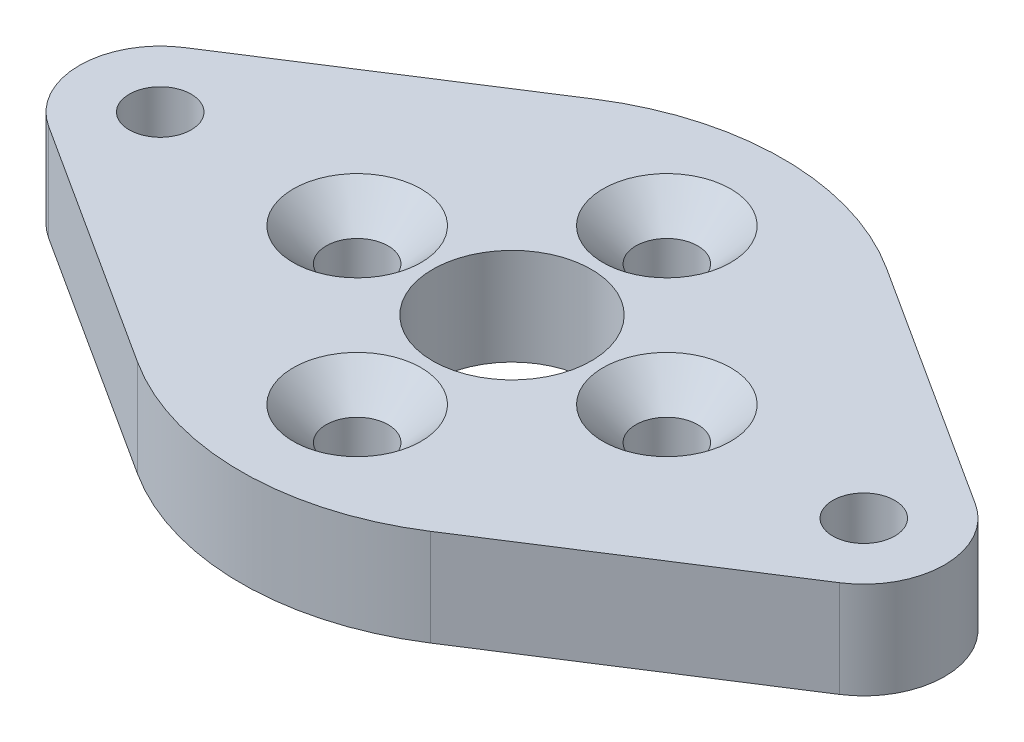
SolidWorks part; units mm, degrees
material "ABS"
ref_plane "Front Plane" through (0, 0, 0) normal (0, 0, 1) x (1, 0, 0)
ref_plane "Top Plane" through (0, 0, 0) normal (0, 1, 0) x (1, 0, 0)
ref_plane "Right Plane" through (0, 0, 0) normal (1, 0, 0) x (0, 0, -1)
sketch "Sketch1" plane through (0, 0, 0) normal (0, 1, 0) x (1, 0, 0)
  line L0 (18.1754, 0) -> (-18.1754, 0) construction
  line L1 (0, 0) -> (0, 8) construction
  line L2 (-20.4324, 3.5129) -> (-7.5676, 11.7784)
  line L3 (-21.3509, 0) -> (-19.7631, -2.75) construction
  line L4 (-19.7631, -2.75) -> (-16.5877, -2.75) construction
  line L5 (-16.5877, -2.75) -> (-15, 0) construction
  line L6 (-15, 0) -> (-16.5877, 2.75) construction
  line L7 (-16.5877, 2.75) -> (-19.7631, 2.75) construction
  line L8 (-19.7631, 2.75) -> (-21.3509, 0) construction
  line L9 (-20.4324, -3.5129) -> (-7.5676, -11.7784)
  line L10 (0, 0) -> (0, 17.7952) construction
  line L11 (20.4324, -3.5129) -> (7.5676, -11.7784)
  line L12 (20.4324, 3.5129) -> (7.5676, 11.7784)
  circle A0 centre (0, 0) radius 8 construction
  circle A1 centre (0, 0) radius 4.1
  arc A6 (-7.5676, -11.7784) -> (7.5676, -11.7784) centre (0, 0) ccw
  circle A7 centre (-18.1754, 0) radius 1.6
  circle A8 centre (18.1754, 0) radius 1.6
  circle A9 centre (-18.1754, 0) radius 2.75 construction
  arc A10 (-20.4324, 3.5129) -> (-20.4324, -3.5129) centre (-18.1754, 0) ccw
  arc A11 (20.4324, 3.5129) -> (20.4324, -3.5129) centre (18.1754, 0) cw
  arc A12 (7.5676, 11.7784) -> (-7.5676, 11.7784) centre (0, 0) ccw
  circle A13 centre (8, 0) radius 1.6
  circle A14 centre (0, 8) radius 1.6
  circle A15 centre (-8, 0) radius 1.6
  circle A16 centre (0, -8) radius 1.6
  point P9 (0, 0)
  dimension "D1" = 16
  dimension "D2" = 8.2
  dimension "D4" = 3.2
  dimension "D6" = 28
  dimension "D7" = 3.2
  dimension "D9" = 15
  dimension "D3" = 90
  dimension "D8" = 5.5
extrude "Boss-Extrude1" add sketch "Sketch1" along normal blind 5
chamfer "Chamfer1" distance 1.7 angle 45 4 edges at (8, 5, 1.6) (0, 5, -6.4) (-8, 5, 1.6) (0, 5, 9.6)
chamfer "Chamfer2" distance 1.7 angle 45 2 edges at (18.1754, 0, 1.6) (-18.1754, 0, 1.6)
